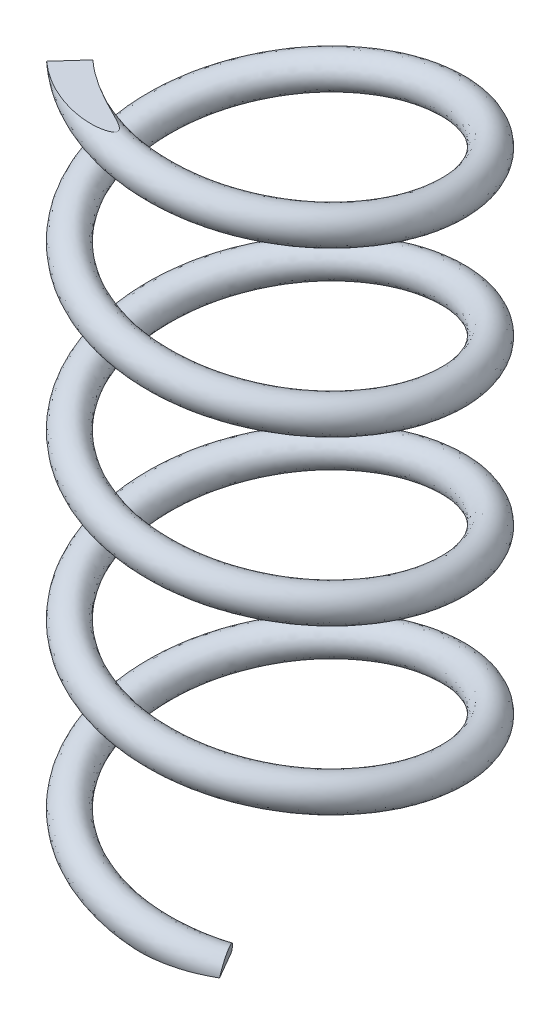
SolidWorks part; units mm, degrees
material "Lega 1060"
ref_plane "Piano frontale" through (0, 0, 0) normal (0, 0, 1) x (1, 0, 0)
ref_plane "Piano superiore" through (0, 0, 0) normal (0, 1, 0) x (1, 0, 0)
ref_plane "Piano destro" through (0, 0, 0) normal (1, 0, 0) x (0, 0, -1)
sketch "Schizzo1" plane through (0, 0, 0) normal (0, 1, 0) x (1, 0, 0)
  circle A0 centre (0, 0) radius 4.55
  dimension "D1" = 9.1
curve "Elica/Spirale1" pitch 5 height 21 turns 4.2
sweep "Sweep1" add path "Elica/Spirale1" circular profile diameter 1 parameters "D3"=1
sketch "Schizzo11" plane through (0, 0, 0) normal (0, 0, 1) x (1, 0, 0)
  line L0 (0, 0) -> (0, 28.9047) construction
sketch "Schizzo12" plane through (0, 0, 0) normal (0, 1, 0) x (1, 0, 0)
  line L1 (-2.4309, -5.4572) -> (2.5359, -5.4572)
  line L2 (-2.4309, -5.4572) -> (-2.4309, -2.9841)
  line L3 (-2.4309, -2.9841) -> (2.5359, -2.9841)
  line L4 (2.5359, -5.4572) -> (2.5359, -2.9841)
  ellipse E0 centre (2.275, -3.9404) end of major axis (2.025, -3.5074) minor radius 0.0861 construction
extrude "Taglio-Estrusione3" cut sketch "Schizzo12" against normal blind 1
ref_plane "Piano2" through (0, 21, 0) normal (0, 1, 0) x (1, 0, 0)
sketch "Schizzo20" plane through (0, 21, 0) normal (0, 1, 0) x (1, 0, 0)
  line L0 (-4.1407, -6.0119) -> (0.2707, -6.0119)
  line L1 (0.2707, -6.0119) -> (0.2707, -2.572)
  line L2 (0.2707, -2.572) -> (-4.1407, -2.572)
  line L3 (-4.1407, -2.572) -> (-4.1407, -6.0119)
extrude "Taglio-Estrusione2" cut sketch "Schizzo20" along normal blind 1
